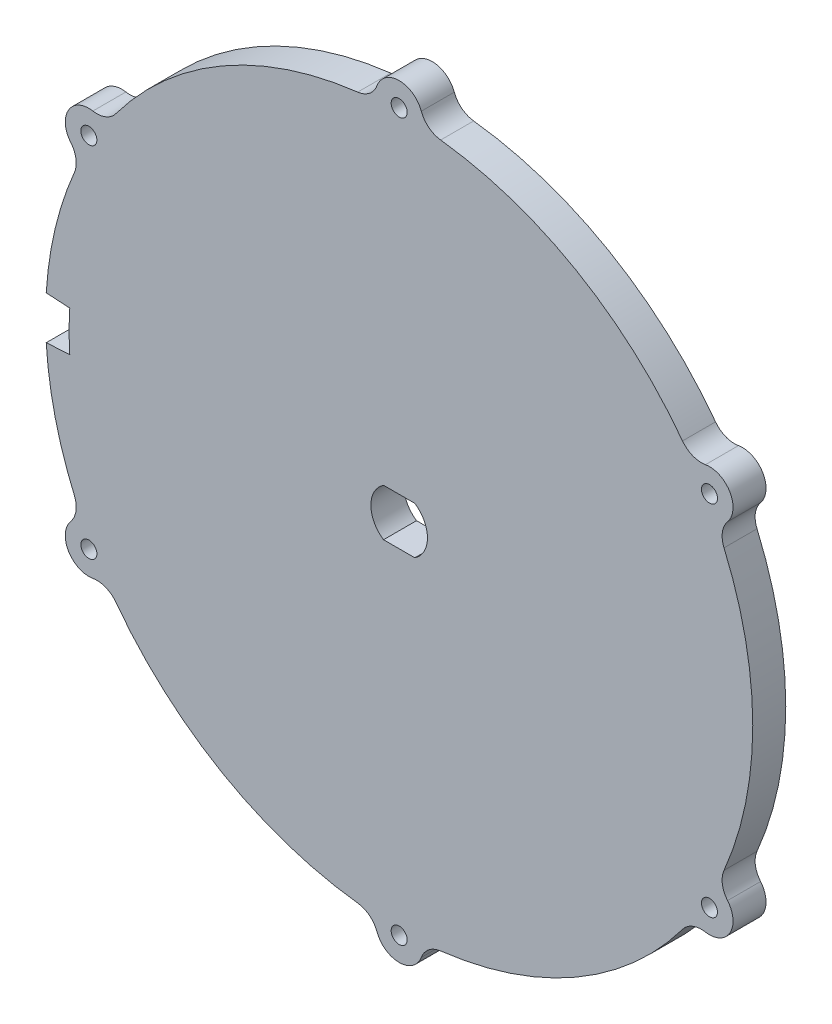
SolidWorks part; units mm, degrees
material "PETG"
ref_plane "Front Plane" through (0, 0, 0) normal (0, 0, 1) x (1, 0, 0)
ref_plane "Top Plane" through (0, 0, 0) normal (0, 1, 0) x (1, 0, 0)
ref_plane "Right Plane" through (0, 0, 0) normal (1, 0, 0) x (0, 0, -1)
sketch "Sketch2" plane through (0, 0, 0) normal (0, 0, 1) x (1, 0, 0)
  line L0 (3.3166, 5) -> (-3.3166, 5)
  line L1 (3.3166, -5) -> (-3.3166, -5)
  circle A0 centre (0, 0) radius 75
  circle A1 centre (0, 0) radius 6
  dimension "D1" = 150
  dimension "D2" = 12
  dimension "D3" = 10
extrude "Boss-Extrude1" add sketch "Sketch2" along normal mid plane 7 contours A0 A1 | L0 A1 | L1 A1
sketch "Sketch4" plane through (0, 0, -3.5) normal (0, 0, 1) x (1, 0, 0)
  line L0 (5, 76) -> (5, 74.8331)
  line L1 (-5, 76) -> (-5, 74.8331)
  arc A0 (5, 76) -> (-5, 76) centre (0, 76) ccw
  circle A1 centre (0, 0) radius 75 construction
  circle A3 centre (0, 0) radius 75
  arc A4 (-5, 74.8331) -> (5, 74.8331) centre (0, 0) ccw
  circle M9 centre (0, 0) radius 75
  dimension "D1" = 5
  dimension "D2" = 76
  dimension "D3" = 0
extrude "Boss-Extrude3" add sketch "Sketch4" along normal up to surface (7 mm away) contours A0 L0 L1 M9 up to face at (0, 0, 3.5)
fillet "Fillet1" radius 5 2 edges at (-5, 74.8331, 0) (5, 74.8331, 0)
sketch "Sketch6" plane through (0, 0, -3.5) normal (0, 0, -1) x (-1, 0, 0)
  circle A0 centre (0, 76) radius 1.7
  arc A4 (4.6935, 77.7237) -> (-4.6935, 77.7237) centre (0, 76) ccw construction
  dimension "D1" = 3.4
extrude "Cut-Extrude1" cut sketch "Sketch6" against normal through all
pattern_circular "CirPattern1" count 6 over 360 about axis through (0, 0, 0) along (0, 0, 1) of "Boss-Extrude3", "Cut-Extrude1", "Fillet1"
sketch "Sketch7" plane through (0, 0, -3.5) normal (0, 0, -1) x (-1, 0, 0)
  line L0 (-5, 59.1608) -> (-5, 22.9129)
  line L1 (5, 59.1608) -> (5, 22.9129)
  line L2 (-5, 19.3649) -> (5, 19.3649) construction
  line L3 (48.7348, 33.9105) -> (17.3431, 15.7866)
  line L4 (53.7348, 25.2503) -> (22.3431, 7.1263)
  line L6 (53.7348, -25.2503) -> (22.3431, -7.1263)
  line L7 (48.7348, -33.9105) -> (17.3431, -15.7866)
  line L9 (5, -59.1608) -> (5, -22.9129)
  line L10 (-5, -59.1608) -> (-5, -22.9129)
  line L12 (-48.7348, -33.9105) -> (-17.3431, -15.7866)
  line L13 (-53.7348, -25.2503) -> (-22.3431, -7.1263)
  line L15 (-53.7348, 25.2503) -> (-22.3431, 7.1263)
  line L16 (-48.7348, 33.9105) -> (-17.3431, 15.7866)
  line L18 (0, 0) -> (8, 18.3303) construction
  line L19 (14.2705, 14.0126) -> (19.2705, 5.3523) construction
  line L20 (19.2705, -5.3523) -> (14.2705, -14.0126) construction
  line L21 (5, -19.3649) -> (-5, -19.3649) construction
  line L22 (-14.2705, -14.0126) -> (-19.2705, -5.3523) construction
  line L23 (-19.2705, 5.3523) -> (-14.2705, 14.0126) construction
  arc A0 (-8, 18.3303) -> (-11.8745, 16.0934) centre (0, 0) ccw
  arc A1 (-10.8333, 64.0909) -> (-50.0876, 41.4274) centre (0, 0) ccw
  arc A2 (5, 22.9129) -> (8, 18.3303) centre (10, 22.9129) ccw
  arc A3 (5, 59.1608) -> (10.8333, 64.0909) centre (10, 59.1608) cw
  arc A4 (-5, 59.1608) -> (-10.8333, 64.0909) centre (-10, 59.1608) ccw
  arc A5 (-5, 22.9129) -> (-8, 18.3303) centre (-10, 22.9129) cw
  arc A6 (22.3431, 7.1263) -> (19.8745, 2.2369) centre (24.8431, 2.7962) ccw
  arc A7 (53.7348, 25.2503) -> (60.921, 22.6635) centre (56.2348, 20.9201) cw
  arc A8 (48.7348, 33.9105) -> (50.0876, 41.4274) centre (46.2348, 38.2407) ccw
  arc A9 (17.3431, 15.7866) -> (11.8745, 16.0934) centre (14.8431, 20.1167) cw
  arc A10 (17.3431, -15.7866) -> (11.8745, -16.0934) centre (14.8431, -20.1167) ccw
  arc A11 (48.7348, -33.9105) -> (50.0876, -41.4274) centre (46.2348, -38.2407) cw
  arc A12 (53.7348, -25.2503) -> (60.921, -22.6635) centre (56.2348, -20.9201) ccw
  arc A13 (22.3431, -7.1263) -> (19.8745, -2.2369) centre (24.8431, -2.7962) cw
  arc A14 (-5, -22.9129) -> (-8, -18.3303) centre (-10, -22.9129) ccw
  arc A15 (-5, -59.1608) -> (-10.8333, -64.0909) centre (-10, -59.1608) cw
  arc A16 (5, -59.1608) -> (10.8333, -64.0909) centre (10, -59.1608) ccw
  arc A17 (5, -22.9129) -> (8, -18.3303) centre (10, -22.9129) cw
  arc A18 (-22.3431, -7.1263) -> (-19.8745, -2.2369) centre (-24.8431, -2.7962) ccw
  arc A19 (-53.7348, -25.2503) -> (-60.921, -22.6635) centre (-56.2348, -20.9201) cw
  arc A20 (-48.7348, -33.9105) -> (-50.0876, -41.4274) centre (-46.2348, -38.2407) ccw
  arc A21 (-17.3431, -15.7866) -> (-11.8745, -16.0934) centre (-14.8431, -20.1167) cw
  arc A22 (-17.3431, 15.7866) -> (-11.8745, 16.0934) centre (-14.8431, 20.1167) ccw
  arc A23 (-48.7348, 33.9105) -> (-50.0876, 41.4274) centre (-46.2348, 38.2407) cw
  arc A24 (-53.7348, 25.2503) -> (-60.921, 22.6635) centre (-56.2348, 20.9201) ccw
  arc A25 (-22.3431, 7.1263) -> (-19.8745, 2.2369) centre (-24.8431, 2.7962) cw
  arc A26 (11.8745, 16.0934) -> (8, 18.3303) centre (0, 0) ccw
  arc A27 (19.8745, -2.2369) -> (19.8745, 2.2369) centre (0, 0) ccw
  arc A28 (8, -18.3303) -> (11.8745, -16.0934) centre (0, 0) ccw
  arc A29 (-11.8745, -16.0934) -> (-8, -18.3303) centre (0, 0) ccw
  arc A30 (-19.8745, 2.2369) -> (-19.8745, -2.2369) centre (0, 0) ccw
  arc A31 (50.0876, 41.4274) -> (10.8333, 64.0909) centre (0, 0) ccw
  arc A32 (60.921, -22.6635) -> (60.921, 22.6635) centre (0, 0) ccw
  arc A33 (10.8333, -64.0909) -> (50.0876, -41.4274) centre (0, 0) ccw
  arc A34 (-50.0876, -41.4274) -> (-10.8333, -64.0909) centre (0, 0) ccw
  arc A35 (-60.921, 22.6635) -> (-60.921, -22.6635) centre (0, 0) ccw
  point P8 (0, 19.3649)
  dimension "D1" = 130
  dimension "D2" = 40
  dimension "D4" = 5
  dimension "D3" = 10
  dimension "D5" = 6
extrude "Cut-Extrude2" cut sketch "Sketch7" against normal blind 2
mirror "Mirror1" [suppressed] about plane through (0, 0, 0) normal (0, 0, 1)
sketch "Sketch9" plane through (0, 0, 0) normal (0, 1, 0) x (1, 0, 0)
  line L0 (-8.8003, 3.5) -> (-60.1031, 3.5) construction
  line L1 (-75, -3.5) -> (-70, -3.5)
  line L2 (-75, -3.5) -> (-75, 3.5)
  line L3 (-75, 3.5) -> (-70, 3.5)
  line L4 (-70, -3.5) -> (-70, 3.5)
  line L5 (-60.1031, -3.5) -> (-8.8003, -3.5) construction
  line L6 (0, 0) -> (0, 49.8627) construction
  line L7 (-68.9034, 3.5) -> (-75, 3.5) construction
  line L8 (-75, 3.5) -> (-75, -3.5) construction
  dimension "D1" = 5
revolve "Cut-Revolve1" cut sketch "Sketch9" angle 7 mid plane about L6
